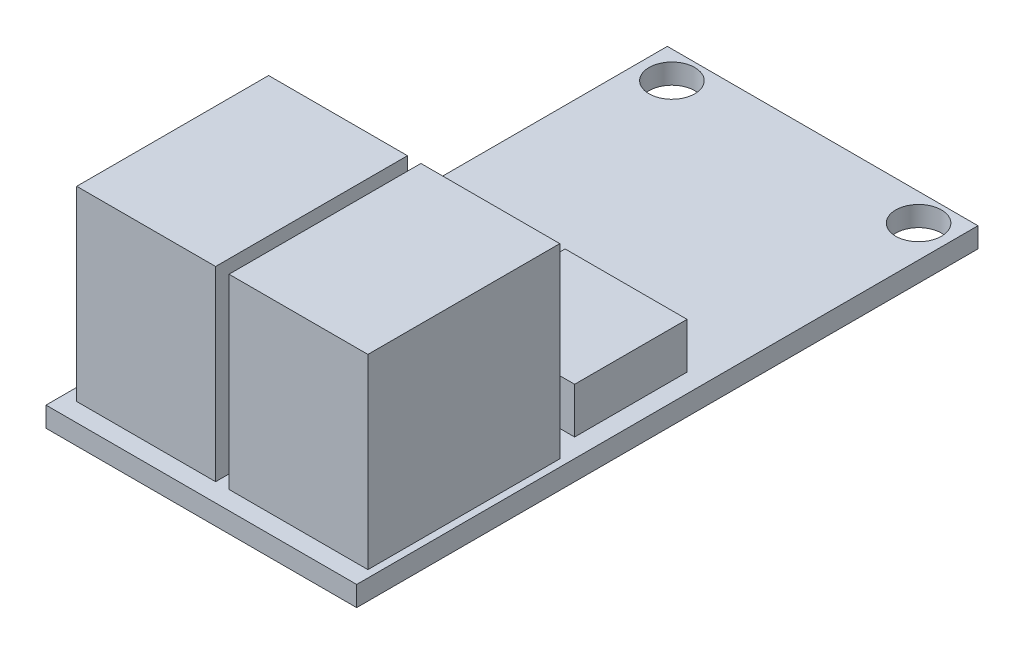
SolidWorks part; units mm, degrees
ref_plane "Front Plane" through (0, 0, 0) normal (0, 0, 1) x (1, 0, 0)
ref_plane "Top Plane" through (0, 0, 0) normal (0, 1, 0) x (1, 0, 0)
ref_plane "Right Plane" through (0, 0, 0) normal (1, 0, 0) x (0, 0, -1)
sketch "Sketch1" plane through (0, 0, 0) normal (0, 1, 0) x (1, 0, 0)
  line L0 (8.5, 34) -> (8.5, 0) construction
  line L1 (0, 0) -> (17, 0)
  line L2 (0, 0) -> (0, 34)
  line L3 (0, 34) -> (17, 34)
  line L4 (17, 0) -> (17, 34)
  line L5 (1.75, 32.5) -> (15.25, 32.5)
  circle A0 centre (1.75, 32.5) radius 1.25
  circle A1 centre (15.25, 32.5) radius 1.25
  point P10 (8.5, 32.5)
  dimension "D4" = 2.5
  dimension "D5" = 2.5
  dimension "D1" = 17
  dimension "D2" = 34
  dimension "D3" = 13.5
  dimension "D6" = 1.5
extrude "Boss-Extrude1" add sketch "Sketch1" along normal blind 1.1
sketch "Sketch2" plane through (0, 1.1, 0) normal (0, 1, 0) x (1, 0, 0)
  line L1 (0.6722, 1.0088) -> (8.2722, 1.0088)
  line L2 (0.6722, 1.0088) -> (0.6722, 11.5088)
  line L3 (0.6722, 11.5088) -> (8.2722, 11.5088)
  line L4 (8.2722, 1.0088) -> (8.2722, 11.5088)
  line L5 (9.0063, 11.5088) -> (16.6063, 11.5088)
  line L6 (9.0063, 11.5088) -> (9.0063, 1.0088)
  line L7 (9.0063, 1.0088) -> (16.6063, 1.0088)
  line L8 (16.6063, 11.5088) -> (16.6063, 1.0088)
  dimension "D1" = 7.6
  dimension "D2" = 7.6
  dimension "D3" = 10.5
  dimension "D4" = 10.5
extrude "Boss-Extrude2" add sketch "Sketch2" along normal blind 10.2 separate body
sketch "Sketch3" plane through (0, 1.1, 0) normal (0, 1, 0) x (1, 0, 0)
  line L1 (1.3342, 19.103) -> (7.7211, 19.103)
  line L2 (1.3342, 19.103) -> (1.3342, 12.9498)
  line L3 (1.3342, 12.9498) -> (7.7211, 12.9498)
  line L4 (7.7211, 19.103) -> (7.7211, 12.9498)
  line L5 (9.3038, 19.103) -> (15.9773, 19.103)
  line L6 (9.3038, 19.103) -> (9.3038, 12.9498)
  line L7 (9.3038, 12.9498) -> (15.9773, 12.9498)
  line L8 (15.9773, 19.103) -> (15.9773, 12.9498)
  point P8 (15.9773, 12.8329)
  point P9 (9.3957, 19.103)
  point P10 (9.3038, 12.9498)
extrude "Boss-Extrude3" add sketch "Sketch3" along normal blind 2.5 separate body
